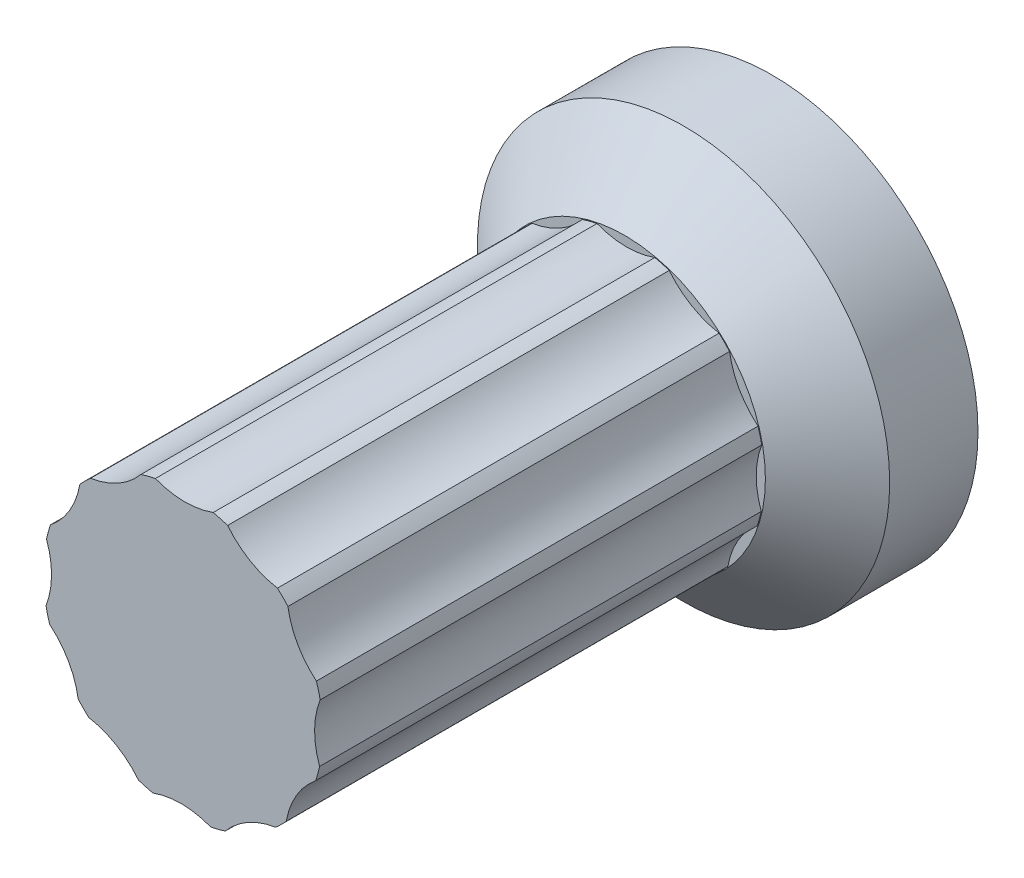
SolidWorks part; units mm, degrees
ref_plane "Alzado" through (0, 0, 0) normal (0, 0, 1) x (1, 0, 0)
ref_plane "Planta" through (0, 0, 0) normal (0, 1, 0) x (1, 0, 0)
ref_plane "Vista lateral" through (0, 0, 0) normal (1, 0, 0) x (0, 0, -1)
sketch "Croquis1" plane through (0, 0, 0) normal (0, 0, 1) x (1, 0, 0)
  circle A0 centre (0, 0) radius 7
  dimension "D1" = 14
extrude "Saliente-Extruir1" add sketch "Croquis1" along normal blind 5
sketch "Croquis2" plane through (0, 0, 5) normal (0, 0, 1) x (1, 0, 0)
  circle A0 centre (0, 0) radius 4.75
  dimension "D1" = 9.5
extrude "Saliente-Extruir2" add sketch "Croquis2" along normal blind 15
chamfer "Chaflán1" distance 2 angle 48 1 edges at (7, 0, 5)
sketch "Croquis3" plane through (0, 0, 20) normal (0, 0, 1) x (1, 0, 0)
  arc A0 (-0.9414, 4.6558) -> (1.0241, 4.6383) centre (0.0645, 7.2471) ccw
  circle A1 centre (0, 0) radius 4.75 construction
  circle A2 centre (0, 0) radius 4.75 construction
  arc A3 (-0.9414, 4.6558) -> (1.0241, 4.6383) centre (0, 0) cw
extrude "Cortar-Extruir1" cut sketch "Croquis3" against normal blind 15
pattern_circular "MatrizC1" count 12 every 30 about axis through (0, 0, 0) along (0, 0, 1) of "Cortar-Extruir1"
